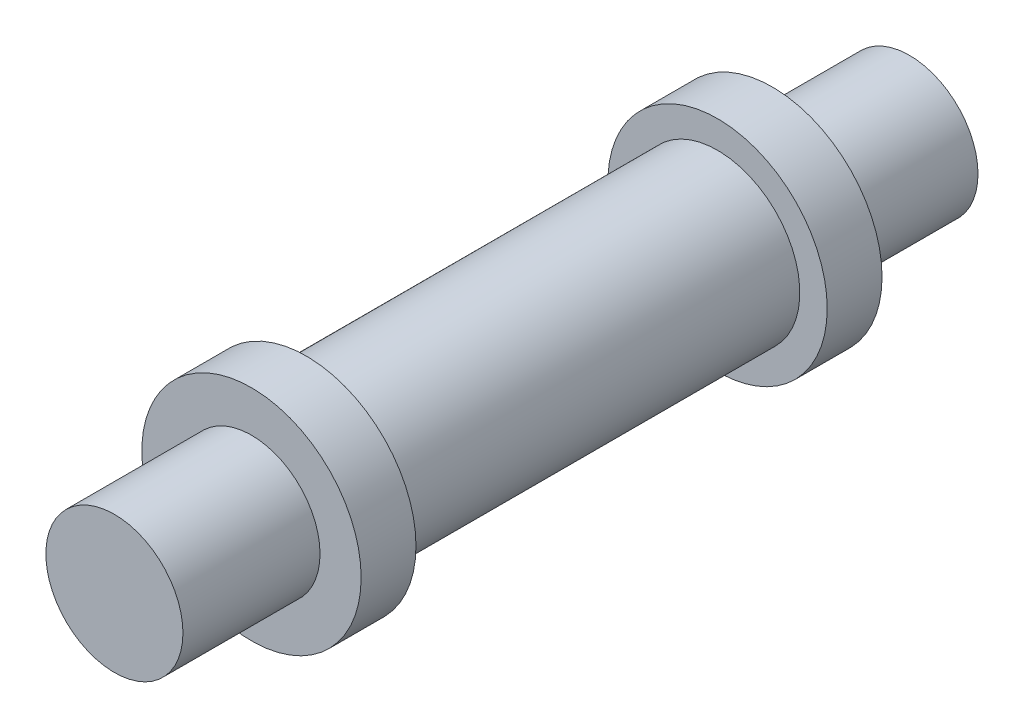
SolidWorks part; units mm, degrees
ref_plane "Front Plane" through (0, 0, 0) normal (0, 0, 1) x (1, 0, 0)
ref_plane "Top Plane" through (0, 0, 0) normal (0, 1, 0) x (1, 0, 0)
ref_plane "Right Plane" through (0, 0, 0) normal (1, 0, 0) x (0, 0, -1)
sketch "Sketch1" plane through (0, 0, 0) normal (0, 0, 1) x (1, 0, 0)
  circle A0 centre (0, 0) radius 3.175
  dimension "D1" = 6.35
extrude "Boss-Extrude1" add sketch "Sketch1" along normal blind 6.35
sketch "Sketch2" plane through (0, 0, 6.35) normal (0, 0, 1) x (1, 0, 0)
  circle A0 centre (0, 0) radius 5.08
  dimension "D1" = 10.16
extrude "Boss-Extrude2" add sketch "Sketch2" along normal blind 2.54
sketch "Sketch3" plane through (0, 0, 8.89) normal (0, 0, 1) x (1, 0, 0)
  circle A0 centre (0, 0) radius 3.81
  dimension "D1" = 7.62
extrude "Boss-Extrude3" add sketch "Sketch3" along normal blind 19.05
sketch "Sketch4" plane through (0, 0, 27.94) normal (0, 0, 1) x (1, 0, 0)
  circle A0 centre (0, 0) radius 5.08
extrude "Boss-Extrude4" add sketch "Sketch4" along normal blind 2.54
sketch "Sketch5" plane through (0, 0, 30.48) normal (0, 0, 1) x (1, 0, 0)
  circle A0 centre (0, 0) radius 3.175
  dimension "D1" = 6.35
extrude "Boss-Extrude5" add sketch "Sketch5" along normal blind 6.35
